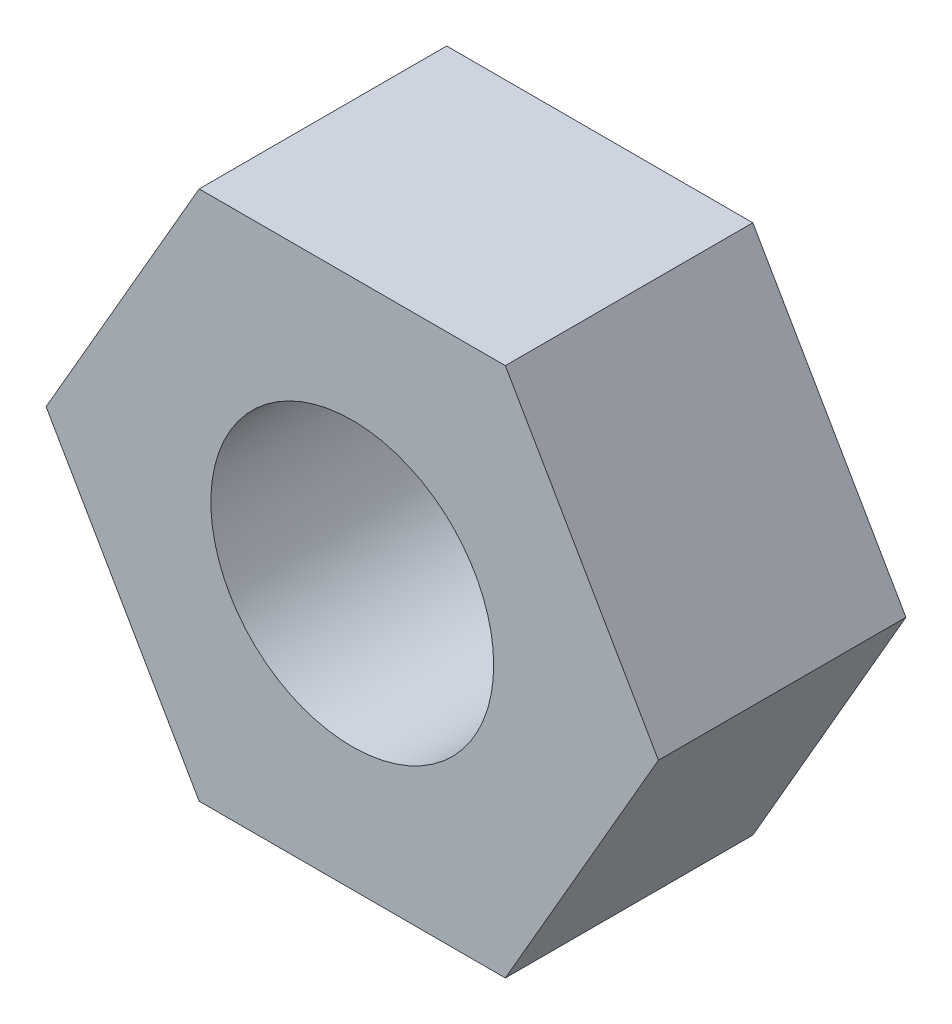
SolidWorks part; units mm, degrees
ref_plane "Alzado" through (0, 0, 0) normal (0, 0, 1) x (1, 0, 0)
ref_plane "Planta" through (0, 0, 0) normal (0, 1, 0) x (1, 0, 0)
ref_plane "Vista lateral" through (0, 0, 0) normal (1, 0, 0) x (0, 0, -1)
sketch "Croquis1" plane through (0, 0, 0) normal (0, 0, 1) x (1, 0, 0)
  line L1 (-4.3301, -7.5) -> (4.3301, -7.5)
  line L2 (4.3301, -7.5) -> (8.6603, 0)
  line L3 (8.6603, 0) -> (4.3301, 7.5)
  line L4 (4.3301, 7.5) -> (-4.3301, 7.5)
  line L5 (-4.3301, 7.5) -> (-8.6603, 0)
  line L6 (-8.6603, 0) -> (-4.3301, -7.5)
  circle A0 centre (0, 0) radius 4
  circle A1 centre (0, 0) radius 7.5 construction
  dimension "D1" = 15
  dimension "D2" = 8
extrude "Saliente-Extruir2" add sketch "Croquis1" along normal blind 7
